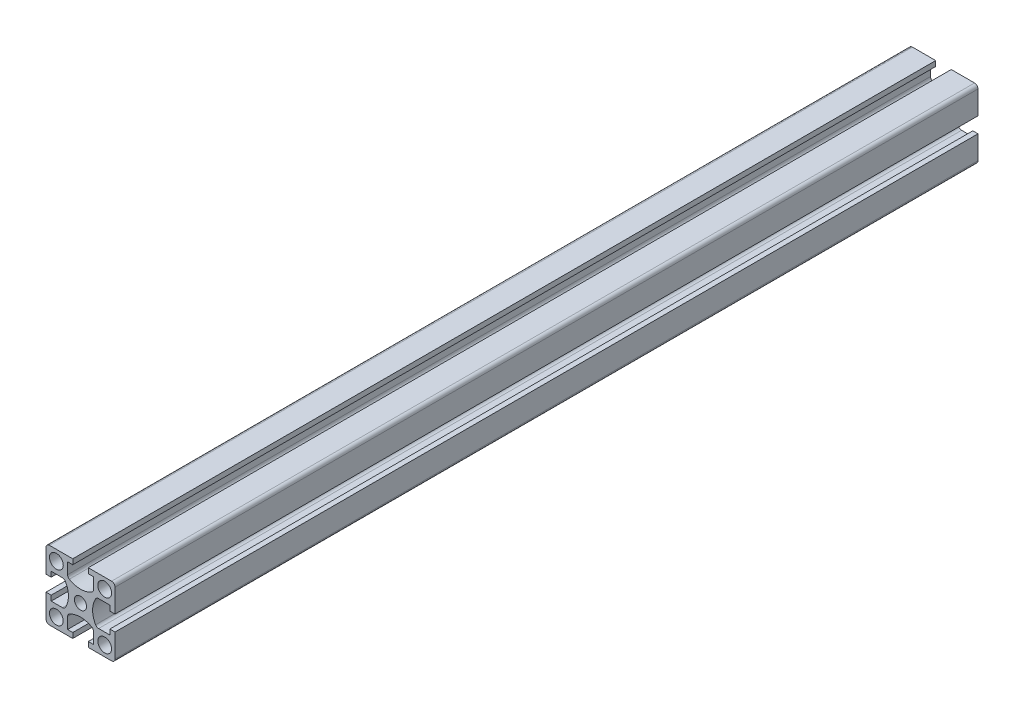
SolidWorks part; units mm, degrees
ref_plane "Front Plane" through (0, 0, 0) normal (0, 0, 1) x (1, 0, 0)
ref_plane "Top Plane" through (0, 0, 0) normal (0, 1, 0) x (1, 0, 0)
ref_plane "Right Plane" through (0, 0, 0) normal (1, 0, 0) x (0, 0, -1)
sketch "Sketch1" plane through (0, 0, 0) normal (0, 0, 1) x (1, 0, 0)
  line L64 (-20, 18) -> (-20, 4.5)
  line L65 (-20, 4.5) -> (-17, 4.5)
  line L66 (-17, 4.5) -> (-17, 7.5)
  line L67 (-17, 7.5) -> (-10.4737, 7.5)
  line L68 (-10.4737, -7.5) -> (-17, -7.5)
  line L69 (-17, -7.5) -> (-17, -4.5)
  line L70 (-17, -4.5) -> (-20, -4.5)
  line L71 (-20, -4.5) -> (-20, -18)
  line L72 (-18, -20) -> (-4.5, -20)
  line L73 (-4.5, -20) -> (-4.5, -17)
  line L74 (-4.5, -17) -> (-7.5, -17)
  line L75 (-7.5, -17) -> (-7.5, -10.4737)
  line L76 (7.5, -10.4737) -> (7.5, -17)
  line L77 (7.5, -17) -> (4.5, -17)
  line L78 (4.5, -17) -> (4.5, -20)
  line L79 (4.5, -20) -> (18, -20)
  line L80 (20, -18) -> (20, -4.5)
  line L81 (20, -4.5) -> (17, -4.5)
  line L82 (17, -4.5) -> (17, -7.5)
  line L83 (17, -7.5) -> (10.4737, -7.5)
  line L84 (10.4737, 7.5) -> (17, 7.5)
  line L85 (17, 7.5) -> (17, 4.5)
  line L86 (17, 4.5) -> (20, 4.5)
  line L87 (20, 4.5) -> (20, 18)
  line L88 (18, 20) -> (4.5, 20)
  line L89 (4.5, 20) -> (4.5, 17)
  line L90 (4.5, 17) -> (7.5, 17)
  line L91 (7.5, 17) -> (7.5, 10.4737)
  line L92 (-7.5, 10.4737) -> (-7.5, 17)
  line L93 (-7.5, 17) -> (-4.5, 17)
  line L94 (-4.5, 17) -> (-4.5, 20)
  line L95 (-4.5, 20) -> (-18, 20)
  circle A5 centre (-14, -14) radius 4
  circle A6 centre (14, -14) radius 4
  circle A7 centre (14, 14) radius 4
  circle A8 centre (0, 0) radius 3.5
  circle A9 centre (-14, 14) radius 4
  arc A32 (-18, 20) -> (-20, 18) centre (-18, 18) ccw
  arc A33 (-8.7417, 6.5) -> (-10.4737, 7.5) centre (-10.4737, 5.5) ccw
  arc A34 (-8.7417, -6.5) -> (-8.7417, 6.5) centre (-20, 0) ccw
  arc A35 (-10.4737, -7.5) -> (-8.7417, -6.5) centre (-10.4737, -5.5) ccw
  arc A36 (-20, -18) -> (-18, -20) centre (-18, -18) ccw
  arc A37 (-6.5, -8.7417) -> (-7.5, -10.4737) centre (-5.5, -10.4737) ccw
  arc A38 (6.5, -8.7417) -> (-6.5, -8.7417) centre (0, -20) ccw
  arc A39 (7.5, -10.4737) -> (6.5, -8.7417) centre (5.5, -10.4737) ccw
  arc A40 (18, -20) -> (20, -18) centre (18, -18) ccw
  arc A41 (8.7417, -6.5) -> (10.4737, -7.5) centre (10.4737, -5.5) ccw
  arc A42 (8.7417, 6.5) -> (8.7417, -6.5) centre (20, 0) ccw
  arc A43 (10.4737, 7.5) -> (8.7417, 6.5) centre (10.4737, 5.5) ccw
  arc A44 (20, 18) -> (18, 20) centre (18, 18) ccw
  arc A45 (6.5, 8.7417) -> (7.5, 10.4737) centre (5.5, 10.4737) ccw
  arc A46 (-6.5, 8.7417) -> (6.5, 8.7417) centre (0, 20) ccw
  arc A47 (-7.5, 10.4737) -> (-6.5, 8.7417) centre (-5.5, 10.4737) ccw
extrude "Boss-Extrude1" add sketch "Sketch1" along normal blind 500
